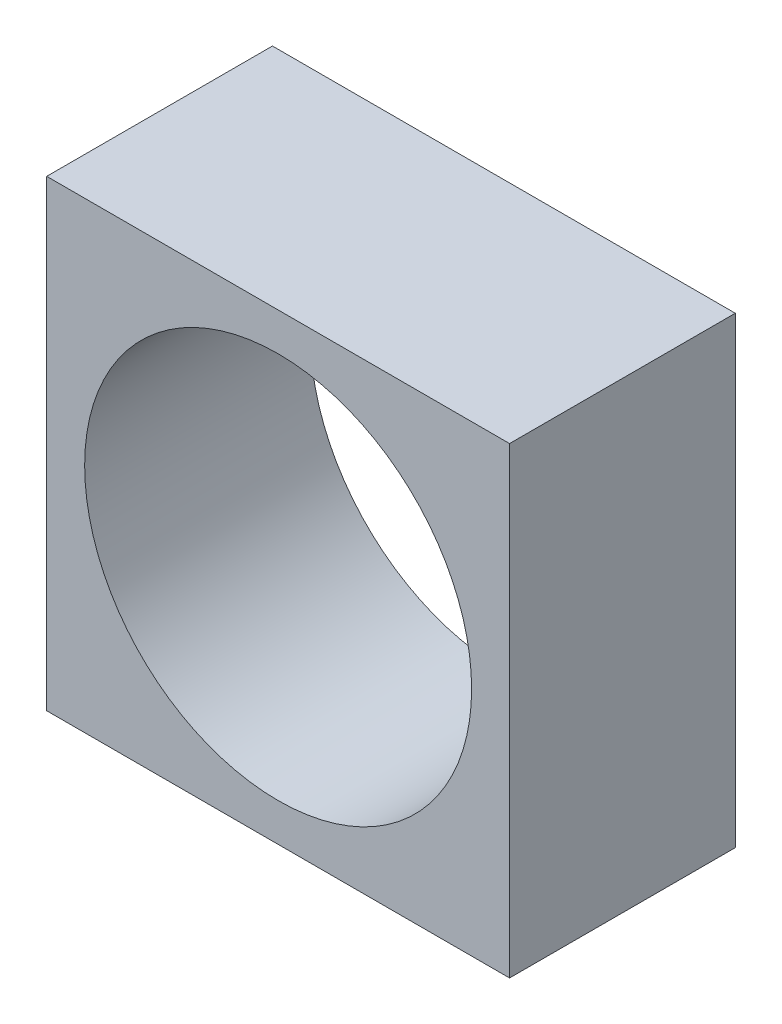
SolidWorks part; units mm, degrees
ref_plane "Front Plane" through (0, 0, 0) normal (0, 0, 1) x (1, 0, 0)
ref_plane "Top Plane" through (0, 0, 0) normal (0, 1, 0) x (1, 0, 0)
ref_plane "Right Plane" through (0, 0, 0) normal (1, 0, 0) x (0, 0, -1)
sketch "Sketch1" plane through (0, 0, 0) normal (0, 0, 1) x (1, 0, 0)
  line L1 (0, 0) -> (6.1, 0)
  line L2 (0, 0) -> (0, 6.1)
  line L3 (0, 6.1) -> (6.1, 6.1)
  line L4 (6.1, 0) -> (6.1, 6.1)
  dimension "D1" = 6.1
  dimension "D2" = 6.1
extrude "Boss-Extrude1" add sketch "Sketch1" along normal blind 2.975
sketch "Sketch2" plane through (0, 0, 2.975) normal (0, 0, 1) x (1, 0, 0)
  line L0 (6.1, 6.1) -> (0, 6.1) construction
  line L1 (0, 6.1) -> (0, 0) construction
  circle A0 centre (3.05, 3.05) radius 2.55
  point P5 (3.05, 6.1)
  point P9 (0, 3.05)
  dimension "D1" = 5.1
extrude "Cut-Extrude1" cut sketch "Sketch2" against normal up to next
